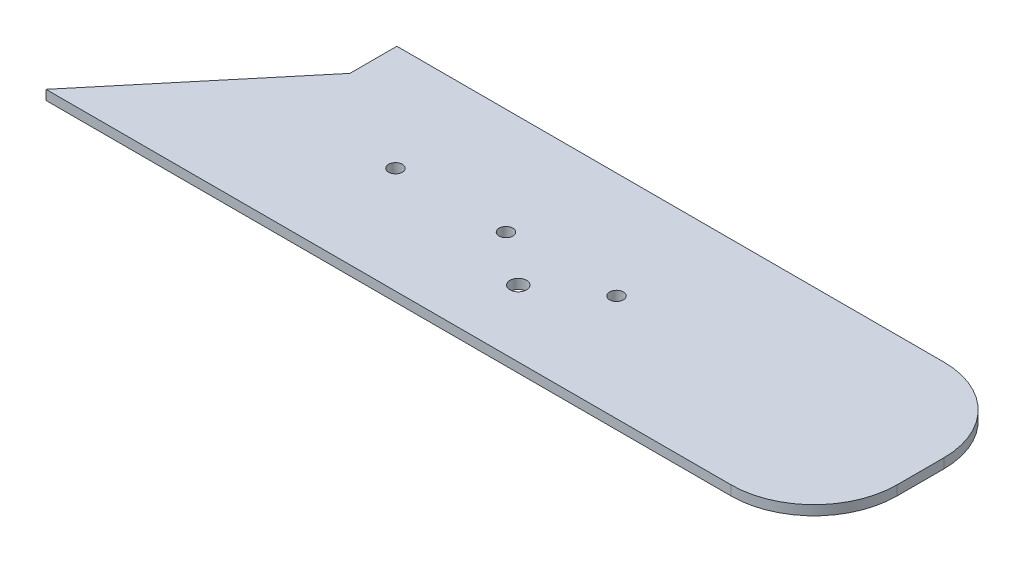
SolidWorks part; units mm, degrees
material "Cast Alloy Steel"
ref_plane "Front Plane" through (0, 0, 0) normal (0, 0, 1) x (1, 0, 0)
ref_plane "Top Plane" through (0, 0, 0) normal (0, 1, 0) x (1, 0, 0)
ref_plane "Right Plane" through (0, 0, 0) normal (1, 0, 0) x (0, 0, -1)
sketch "Sketch1" plane through (0, 0, 0) normal (0, 1, 0) x (1, 0, 0)
  line L0 (-18.0847, -7.9825) -> (229.9153, -7.9825)
  line L1 (259.9153, 22.0175) -> (259.9153, 39.0175)
  line L2 (229.9153, 69.0175) -> (31.9153, 69.0175)
  line L4 (31.9153, 69.0175) -> (31.9153, 65.5175)
  line L6 (31.9153, 65.5175) -> (31.9153, 52.0175)
  line L11 (-18.0847, -7.9825) -> (31.9153, 52.0175)
  circle A0 centre (149.9153, 30.5175) radius 2.5
  circle A1 centre (109.9153, 30.5175) radius 2.5
  circle A2 centre (69.9153, 30.5175) radius 2.5
  arc A3 (259.9153, 39.0175) -> (229.9153, 69.0175) centre (229.9153, 39.0175) ccw
  arc A4 (229.9153, -7.9825) -> (259.9153, 22.0175) centre (229.9153, 22.0175) ccw
  point P12 (259.9153, 69.0175)
  point P15 (259.9153, -7.9825)
  dimension "D1" = 30
  dimension "D7" = 30
  dimension "D2" = 40
  dimension "D4" = 77
  dimension "D5" = 228
  dimension "D6" = 40
  dimension "D8" = 17
  dimension "D9" = 50
extrude "Boss-Extrude3" add sketch "Sketch1" along normal blind 3.5
hole_wizard "Ø6.0mm Dowel Hole1" positions "Sketch2" profile "Sketch3" hole size "Ø6.0" standard "ANSI Metric"
sketch "Sketch2" plane through (224.54, 261.5, -21.5445) normal (0, 1, 0) x (1, 0, 0)
  point P0 (-166.162, -5.4146)
sketch "Sketch3" plane through (58.378, 261.5, -16.1298) normal (1, 0, 0) x (0, 0, 1)
  line L0 (0, 0) -> (0, 261.5)
  line L1 (0, 261.5) -> (3, 261.5)
  line L2 (3, 261.5) -> (3, 0)
  line L3 (3, 0) -> (0, 0)
  line L4 (0, -6.35) -> (0, 107.95) construction
  dimension "Thru Hole Dia." = 6
  dimension "Thru Hole Depth" = 261.5
hole_wizard "Ø6.0mm Dowel Hole2" positions "Sketch4" profile "Sketch5" hole size "Ø6.0" standard "ANSI Metric"
sketch "Sketch4" plane through (224.54, 261.5, -21.5445) normal (0, 1, 0) x (1, 0, 0)
  point P0 (-166.1755, 27.5457)
sketch "Sketch5" plane through (58.3645, 261.5, -49.0902) normal (1, 0, 0) x (0, 0, 1)
  line L0 (0, 0) -> (0, 261.5)
  line L1 (0, 261.5) -> (3, 261.5)
  line L2 (3, 261.5) -> (3, 0)
  line L3 (3, 0) -> (0, 0)
  line L4 (0, -6.35) -> (0, 107.95) construction
  dimension "Thru Hole Dia." = 6
  dimension "Thru Hole Depth" = 261.5
hole_wizard "Ø6.0mm Dowel Hole3" positions "Sketch6" profile "Sketch7" hole size "Ø6.0" standard "ANSI Metric"
sketch "Sketch6" plane through (224.54, 261.5, -21.5445) normal (0, 1, 0) x (1, 0, 0)
  point P0 (-95.7972, 27.5475)
sketch "Sketch7" plane through (128.7428, 261.5, -49.092) normal (1, 0, 0) x (0, 0, 1)
  line L0 (0, 0) -> (0, 261.5)
  line L1 (0, 261.5) -> (3, 261.5)
  line L2 (3, 261.5) -> (3, 0)
  line L3 (3, 0) -> (0, 0)
  line L4 (0, -6.35) -> (0, 107.95) construction
  dimension "Thru Hole Dia." = 6
  dimension "Thru Hole Depth" = 261.5
hole_wizard "Ø6.0mm Dowel Hole4" positions "Sketch8" profile "Sketch9" hole size "Ø6.0" standard "ANSI Metric" end condition through all
sketch "Sketch8" plane through (224.54, 261.5, -21.5445) normal (0, 1, 0) x (1, 0, 0)
  point P0 (-95.7972, -5.4146)
sketch "Sketch9" plane through (128.7428, 261.5, -16.1298) normal (1, 0, 0) x (0, 0, 1)
  line L0 (0, 0) -> (0, 261.5)
  line L1 (0, 261.5) -> (3, 261.5)
  line L2 (3, 261.5) -> (3, 0)
  line L3 (3, 0) -> (0, 0)
  line L4 (0, -6.35) -> (0, 107.95) construction
  dimension "Thru Hole Dia." = 6
  dimension "Thru Hole Depth" = 261.5
